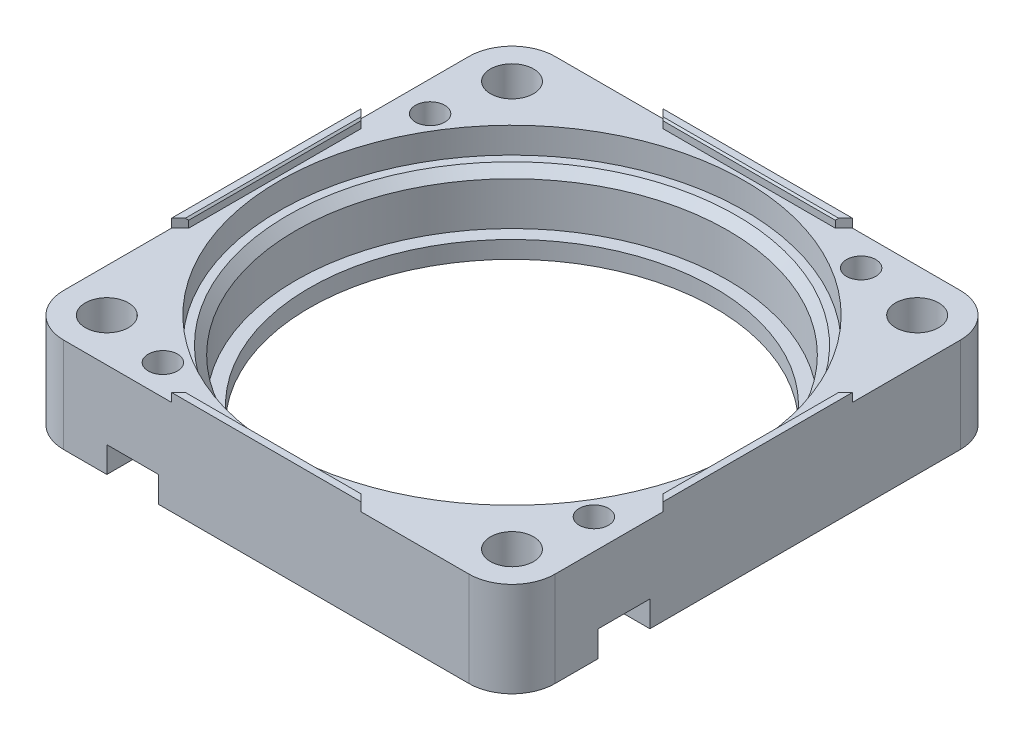
SolidWorks part; units mm, degrees
ref_plane "前视基准面" through (0, 0, 0) normal (0, 0, 1) x (1, 0, 0)
ref_plane "上视基准面" through (0, 0, 0) normal (0, 1, 0) x (1, 0, 0)
ref_plane "右视基准面" through (0, 0, 0) normal (1, 0, 0) x (0, 0, -1)
sketch "草图1" plane through (0, 0, 0) normal (0, 1, 0) x (1, 0, 0)
  line L1 (-28.5, -28.5) -> (28.5, -28.5)
  line L2 (-28.5, -28.5) -> (-28.5, 28.5)
  line L3 (-28.5, 28.5) -> (28.5, 28.5)
  line L4 (28.5, -28.5) -> (28.5, 28.5)
  line L5 (-28.5, -28.5) -> (28.5, 28.5) construction
  line L6 (-28.5, 28.5) -> (28.5, -28.5) construction
  point P0 (0, 0)
  dimension "D1" = 57
extrude "凸台-拉伸1" add sketch "草图1" along normal blind 11
fillet "圆角1" radius 5 4 edges at (-28.5, 5.5, -28.5) (-28.5, 5.5, 28.5) (28.5, 5.5, -28.5) (28.5, 5.5, 28.5)
sketch "草图2" plane through (0, 11, 0) normal (0, 1, 0) x (1, 0, 0)
  circle A0 centre (0, 0) radius 27
  dimension "D1" = 54
extrude "切除-拉伸1" cut sketch "草图2" against normal blind 3
sketch "草图3" plane through (0, 8, 0) normal (0, 1, 0) x (1, 0, 0)
  circle A0 centre (0, 0) radius 25.05
  dimension "D1" = 50.1
extrude "切除-拉伸2" cut sketch "草图3" against normal blind 6
sketch "草图4" plane through (0, 2, 0) normal (0, 1, 0) x (1, 0, 0)
  circle A0 centre (0, 0) radius 23.5
  dimension "D1" = 47
extrude "切除-拉伸3" cut sketch "草图4" against normal blind 2
chamfer "倒角1" distance 1 angle 45 1 edges at (0, 8, 25.05)
sketch "草图5" plane through (0, 11, 0) normal (0, 1, 0) x (1, 0, 0)
  line L0 (-23.5, 23.5) -> (0, 0) construction
  line L1 (0, 0) -> (0, -50000) construction
  line L2 (-28.5, 23.5) -> (-28.5, -23.5) construction
  circle A0 centre (-23.5, 23.5) radius 2.5
  circle A1 centre (-25, 15.5) radius 1.7
  dimension "D2" = 5
  dimension "D4" = 8
  dimension "D5" = 3.5
  dimension "D6" = 3.4
  dimension "D1" = 45
  dimension "D3" = 47
extrude "切除-拉伸4" cut sketch "草图5" against normal through all
sketch "草图6" plane through (0, 11, 0) normal (0, 1, 0) x (1, 0, 0)
  line L0 (-28.5, 11) -> (-28.5, -11)
  line L1 (-28.5, 23.5) -> (-28.5, -23.5) construction
  line L2 (-28.5, -11) -> (-27.5, -10)
  line L3 (-27.5, -10) -> (-27.5, 10)
  line L4 (-27.5, 10) -> (-28.5, 11)
  line L5 (-27.5, 0) -> (0, 0) construction
  dimension "D1" = 135
  dimension "D2" = 135
  dimension "D3" = 22
  dimension "D4" = 1
extrude "凸台-拉伸2" add sketch "草图6" along normal blind 1
chamfer "倒角2" distance 0.2 angle 45 1 edges at (-27.5, 12, 0)
sketch "草图7" plane through (0, 0, 0) normal (0, -1, 0) x (1, 0, 0)
  line L0 (-25, -15.5) -> (-30.8182, -15.5) construction
  line L1 (-25, -18.5) -> (-30.8182, -18.5)
  line L2 (-25, -12.5) -> (-30.8182, -12.5)
  arc A0 (-25, -18.5) -> (-25, -12.5) centre (-25, -15.5) ccw
  arc A1 (-30.8182, -12.5) -> (-30.8182, -18.5) centre (-30.8182, -15.5) ccw
  point P3 (-27.9091, -15.5)
  dimension "D1" = 6
extrude "切除-拉伸5" cut sketch "草图7" against normal blind 3
pattern_circular "阵列(圆周)1" count 4 over 360 about axis through (0, 0, 0) along (0, 1, 0) of "切除-拉伸4", "切除-拉伸5", "凸台-拉伸2", "倒角2"
